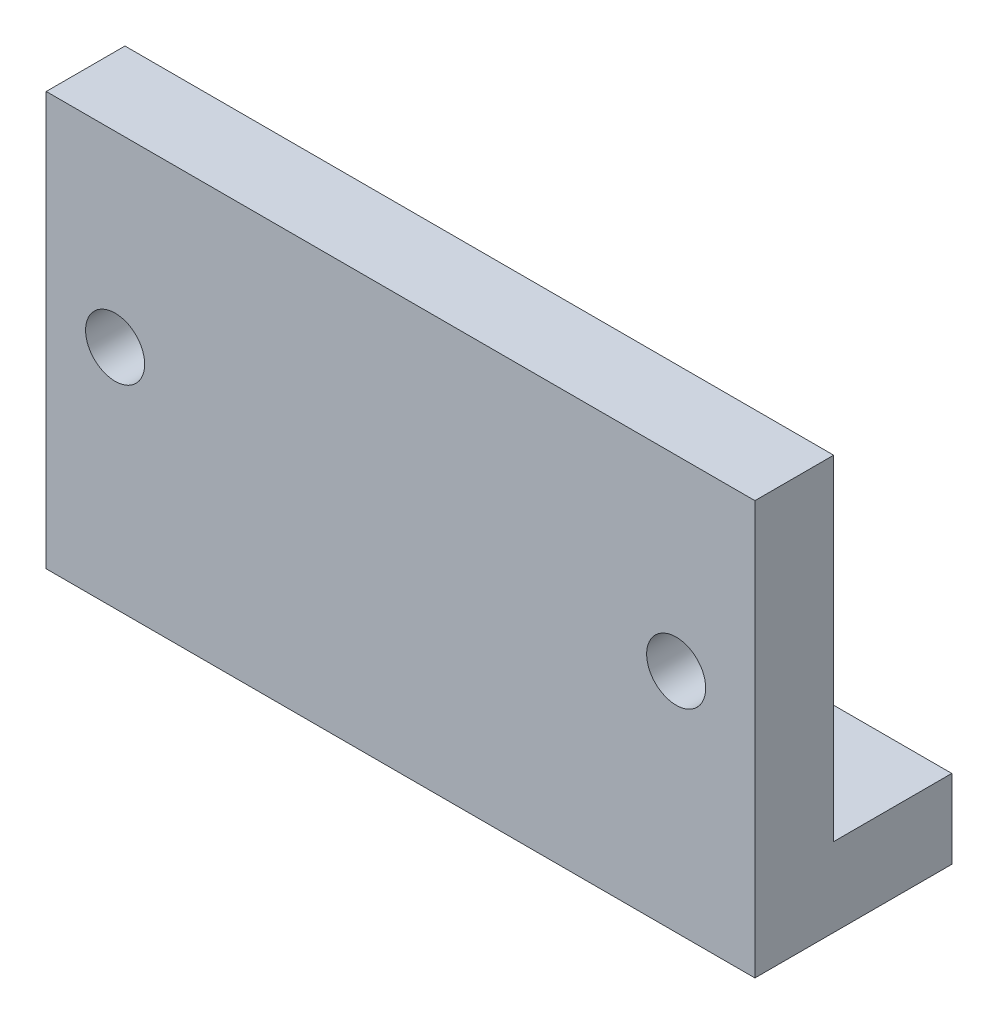
SolidWorks part; units mm, degrees
ref_plane "Alzado" through (0, 0, 0) normal (0, 0, 1) x (1, 0, 0)
ref_plane "Planta" through (0, 0, 0) normal (0, 1, 0) x (1, 0, 0)
ref_plane "Vista lateral" through (0, 0, 0) normal (1, 0, 0) x (0, 0, -1)
sketch "Croquis1" plane through (0, 0, 0) normal (0, 1, 0) x (1, 0, 0)
  line L1 (0, 0) -> (-36, 0)
  line L2 (0, 0) -> (0, -10)
  line L3 (0, -10) -> (-36, -10)
  line L4 (-36, 0) -> (-36, -10)
  dimension "D1" = 10
  dimension "D2" = 36
extrude "Saliente-Extruir1" add sketch "Croquis1" along normal blind 7
sketch "Croquis3" plane through (0, 7, 0) normal (0, 1, 0) x (1, 0, 0)
  line L0 (-36, 0) -> (-36, -10) construction
  line L1 (0, -10) -> (-36, -10)
  line L2 (0, -10) -> (0, -6)
  line L3 (0, -6) -> (-36, -6)
  line L4 (-36, -10) -> (-36, -6)
  dimension "D1" = 4
extrude "Saliente-Extruir2" add sketch "Croquis3" along normal blind 14
sketch "Croquis4" plane through (0, 7, 0) normal (0, 1, 0) x (1, 0, 0)
  line L0 (-18, 7.7666) -> (-18, -18.7722) construction
  line L1 (0, -6) -> (0, 0) construction
  line L2 (-36, 0) -> (-36, -6) construction
  line L3 (0, -6) -> (-36, -6) construction
  circle A0 centre (-30, -3) radius 1.5
  circle A1 centre (-18, -3) radius 1.5
  circle A2 centre (-6, -3) radius 1.5
  dimension "D1" = 3
  dimension "D2" = 12
  dimension "D3" = 12
  dimension "D4" = 3
extrude "Cortar-Extruir1" cut sketch "Croquis4" against normal blind 10
sketch "Croquis5" plane through (0, 0, 10) normal (0, 0, 1) x (1, 0, 0)
  line L0 (-36, 0) -> (0, 0) construction
  line L1 (-18, 22.8686) -> (-18, -5.3583) construction
  line L2 (0, 21) -> (0, 0) construction
  line L3 (-36, 21) -> (-36, 0) construction
  circle A0 centre (-32.5, 11.5) radius 1.5
  circle A1 centre (-4, 11.5) radius 1.5
  dimension "D1" = 11.5
  dimension "D2" = 3
  dimension "D3" = 28.5
  dimension "D4" = 3.5
extrude "Cortar-Extruir2" cut sketch "Croquis5" against normal blind 10
sketch "Croquis6" plane through (0, 0, 0) normal (0, 0, -1) x (-1, 0, 0)
  line L0 (36, 7) -> (36, 0) construction
  line L1 (0, 7) -> (36, 7)
  line L2 (0, 7) -> (0, 4)
  line L3 (0, 4) -> (36, 4)
  line L4 (36, 7) -> (36, 4)
  dimension "D1" = 3
extrude "Cortar-Extruir3" cut sketch "Croquis6" against normal blind 6
